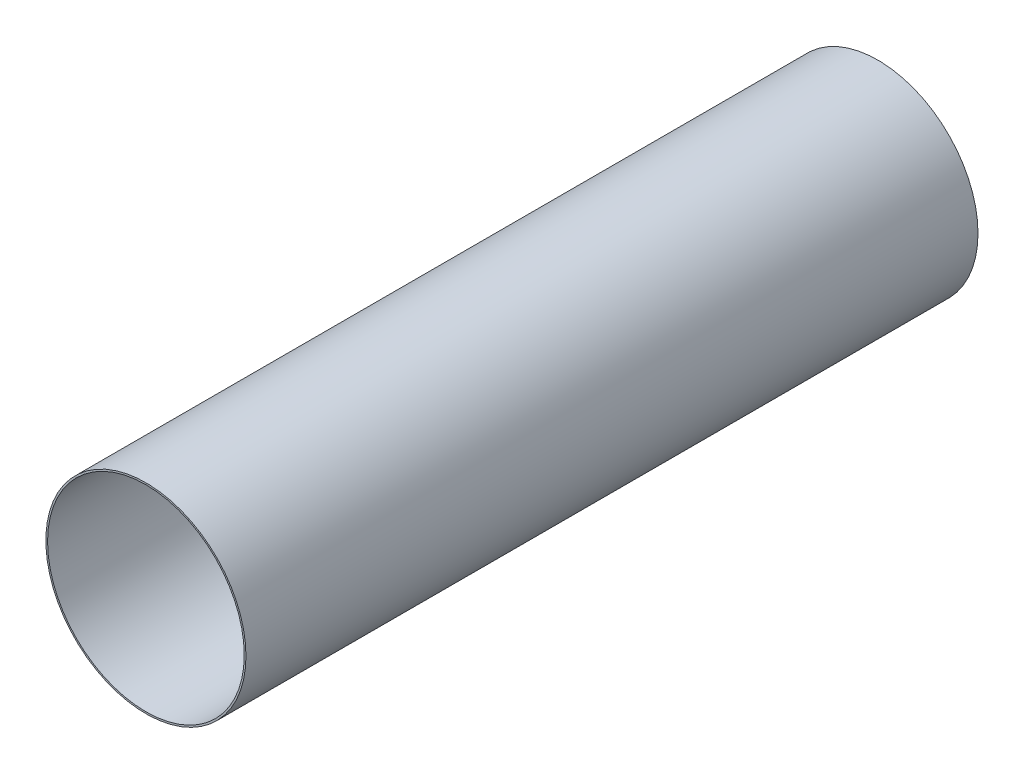
SolidWorks part; units mm, degrees
material "Простая углеродистая сталь"
ref_plane "Спереди" through (0, 0, 0) normal (0, 0, 1) x (1, 0, 0)
ref_plane "Сверху" through (0, 0, 0) normal (0, 1, 0) x (1, 0, 0)
ref_plane "Справа" through (0, 0, 0) normal (1, 0, 0) x (0, 0, -1)
sketch "Эскиз1" plane through (0, 0, 0) normal (0, 0, 1) x (1, 0, 0)
  circle A0 centre (0, 0) radius 115
extrude "Бобышка-Вытянуть1" add sketch "Эскиз1" against normal blind 856
shell "Оболочка2" thickness 2
